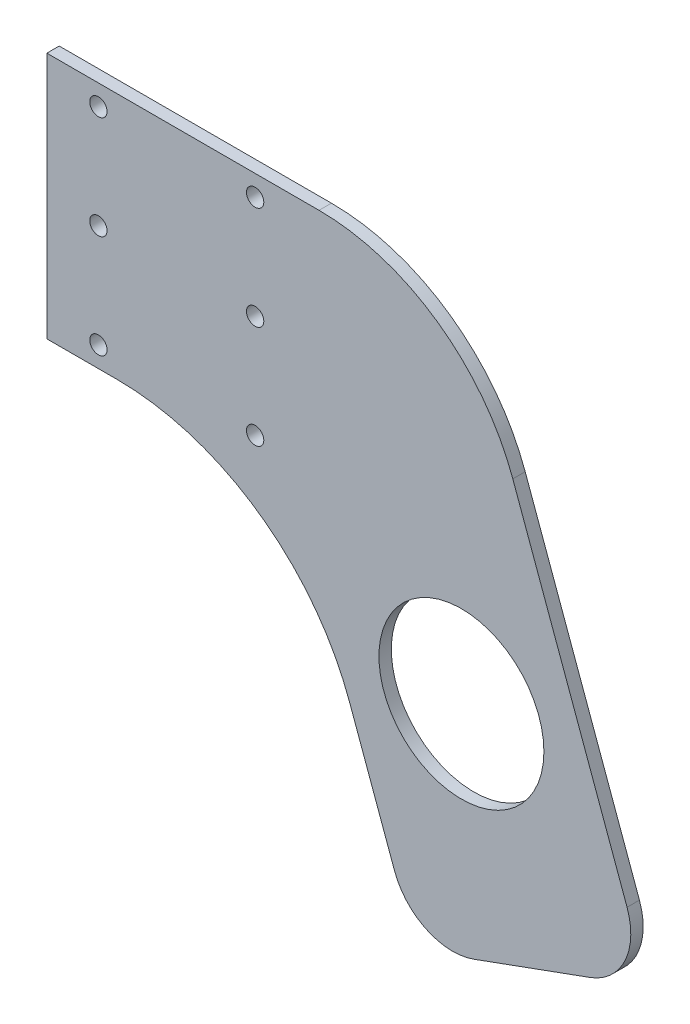
SolidWorks part; units mm, degrees
ref_plane "Front Plane" through (0, 0, 0) normal (0, 0, 1) x (1, 0, 0)
ref_plane "Top Plane" through (0, 0, 0) normal (0, 1, 0) x (1, 0, 0)
ref_plane "Right Plane" through (0, 0, 0) normal (1, 0, 0) x (0, 0, -1)
sketch "Sketch1" plane through (0, 0, 0) normal (0, 0, 1) x (1, 0, 0)
  line L0 (0, 0) -> (0, 50000) construction
  line L1 (0, 0) -> (50000, 0) construction
  line L2 (0, 56.5646) -> (-80, 56.5646) construction
  line L3 (0, 56.5646) -> (20.5212, 0.1831) construction
  line L4 (20.5212, 0.1831) -> (42.5081, -60.2255) construction
  line L5 (-80, 26.5646) -> (-80, 86.5646)
  line L6 (-80, 86.5646) -> (0, 86.5646)
  line L7 (-80, 26.5646) -> (-21.0062, 26.5646)
  line L8 (21.0062, 86.5646) -> (65.813, -36.541)
  line L9 (0, 86.5646) -> (21.0062, 86.5646)
  line L10 (-21.0062, 26.5646) -> (-21.0062, 86.5646) construction
  line L11 (-21.0062, 26.5646) -> (9.4314, -57.0622)
  line L12 (9.4314, -57.0622) -> (65.813, -36.541)
  line L13 (-67.5, 86.5646) -> (-67.5, 26.5646) construction
  line L14 (-29.5, 86.5646) -> (-29.5, 26.5646) construction
  circle A0 centre (20.5212, 0.1831) radius 20
  circle A1 centre (-67.5, 81.5646) radius 2.1
  circle A2 centre (-67.5, 56.5646) radius 2.1
  circle A3 centre (-67.5, 31.5646) radius 2.1
  circle A4 centre (-29.5, 81.5646) radius 2.1
  circle A5 centre (-29.5, 56.5646) radius 2.1
  circle A6 centre (-29.5, 31.5646) radius 2.1
  dimension "D7" = 40
  dimension "D10" = 4.2
  dimension "D1" = 110
  dimension "D2" = 60
  dimension "D3" = 80
  dimension "D4" = 30
  dimension "D5" = 30
  dimension "D6" = 50
  dimension "D8" = 58.9938
  dimension "D9" = 12.5
  dimension "D11" = 5
  dimension "D12" = 5
  dimension "D13" = 38
extrude "Boss-Extrude1" add sketch "Sketch1" along normal blind 3
fillet "Fillet1" radius 50 1 edges at (21.0062, 86.5646, 1.5)
fillet "Fillet2" radius 60 1 edges at (-21.0062, 26.5646, 1.5)
fillet "Fillet3" radius 15 2 edges at (65.813, -36.541, 1.5) (9.4314, -57.0622, 1.5)
